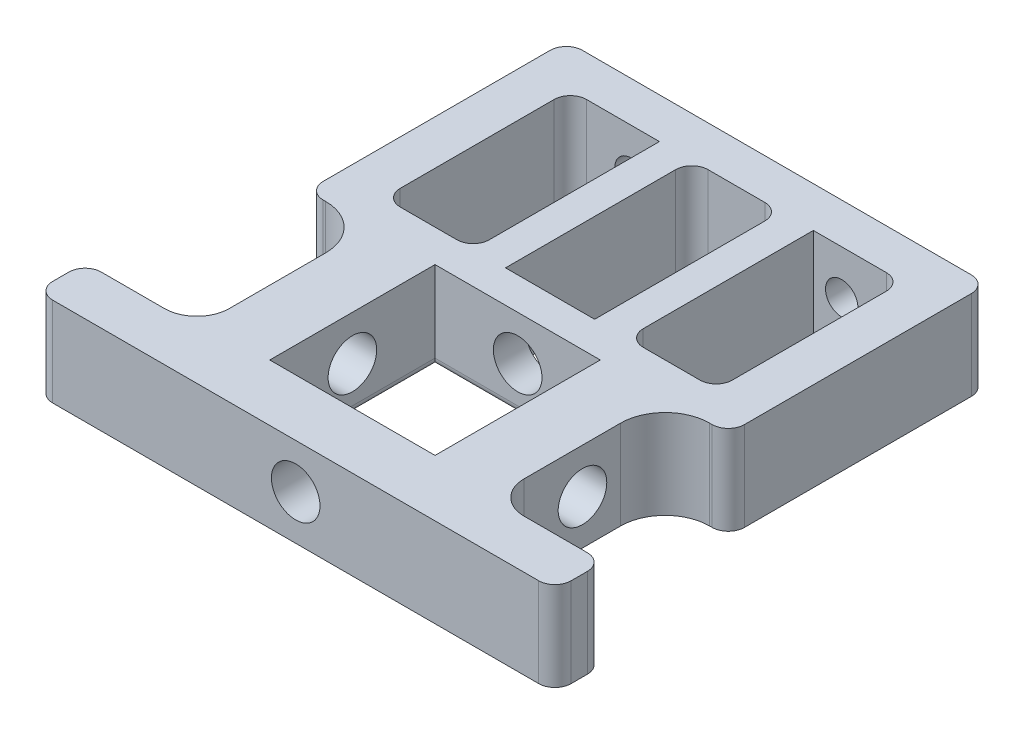
SolidWorks part; units mm, degrees
ref_plane "Front Plane" through (0, 0, 0) normal (0, 0, 1) x (1, 0, 0)
ref_plane "Top Plane" through (0, 0, 0) normal (0, 1, 0) x (1, 0, 0)
ref_plane "Right Plane" through (0, 0, 0) normal (1, 0, 0) x (0, 0, -1)
sketch "Sketch1" plane through (0, 0, 0) normal (0, 1, 0) x (1, 0, 0)
  line L0 (26, 0) -> (26, -32) construction
  line L1 (0, 0) -> (52, 0)
  line L2 (0, 0) -> (0, -32)
  line L3 (0, -32) -> (52, -32)
  line L4 (52, 0) -> (52, -32)
  line L5 (13, 8.9891) -> (13, -5) construction
  line L6 (20.5, -5) -> (31.5, -5)
  line L7 (20.5, -5) -> (20.5, -28)
  line L8 (20.5, -28) -> (31.5, -28)
  line L9 (31.5, -5) -> (31.5, -28)
  line L10 (46.5, -28) -> (35.5, -28)
  line L11 (5.5, -5) -> (16.5, -5)
  line L12 (5.5, -5) -> (5.5, -28)
  line L13 (5.5, -28) -> (16.5, -28)
  line L14 (16.5, -5) -> (16.5, -28)
  line L15 (15.8, -32) -> (36.2, -32)
  line L16 (15.8, -32) -> (15.8, -52.4)
  line L17 (15.8, -52.4) -> (36.2, -52.4)
  line L18 (36.2, -32) -> (36.2, -52.4)
  line L19 (7.8, -32) -> (44.2, -32)
  line L20 (7.8, -32) -> (7.8, -59.4)
  line L21 (7.8, -59.4) -> (44.2, -59.4)
  line L22 (44.2, -32) -> (44.2, -59.4)
  line L23 (35.5, -5) -> (35.5, -28)
  line L24 (46.5, -5) -> (35.5, -5)
  line L25 (46.5, -5) -> (46.5, -28)
  dimension "D1" = 52
  dimension "D2" = 32
  dimension "D3" = 5.5
  dimension "D4" = 5.5
  dimension "D5" = 5
  dimension "D6" = 4
  dimension "D7" = 13
  dimension "D8" = 5
  dimension "D9" = 4
  dimension "D10" = 4
  dimension "D11" = 5.5
  dimension "D12" = 10.2
  dimension "D13" = 10.2
  dimension "D14" = 20.4
  dimension "D15" = 8
  dimension "D16" = 8
  dimension "D17" = 7
extrude "Boss-Extrude1" add sketch "Sketch1" along normal blind 11 contours L4 L1 L2 L3 L6 L9 L8 L7 L11 L14 L13 L12 L24 L25 L10 L23 | L22 L3 L18 L17 L16 L20 L21
sketch "Sketch2" plane through (0, 0, 0) normal (0, 0, -1) x (-1, 0, 0)
  line L0 (-26, 11) -> (-26, 0) construction
  line L1 (0, 11) -> (-52, 11) construction
  line L2 (0, 0) -> (-52, 0) construction
  line L3 (-39, 11) -> (-39, 0) construction
  line L4 (-52, 5.5) -> (0, 5.5) construction
  line L5 (-52, 11) -> (-52, 0) construction
  line L6 (0, 11) -> (0, 0) construction
  circle A0 centre (-39, 5.5) radius 2
  circle A1 centre (-13, 5.5) radius 2
  dimension "D1" = 13
extrude "Cut-Extrude1" cut sketch "Sketch2" against normal up to next
sketch "Sketch3" plane through (15.8, 0, 0) normal (1, 0, 0) x (0, 0, -1)
  line L0 (-42.2, 0) -> (-42.2, 11) construction
  line L1 (-32, 0) -> (-52.4, 0) construction
  line L2 (-32, 11) -> (-52.4, 11) construction
  line L3 (-32, 5.5) -> (-52.4, 5.5) construction
  line L4 (-32, 11) -> (-32, 0) construction
  line L5 (-52.4, 11) -> (-52.4, 0) construction
  circle A0 centre (-42.2, 5.5) radius 3
  dimension "D1" = 6
extrude "Cut-Extrude2" cut sketch "Sketch3" against normal up to next and the other way up to next
sketch "Sketch4" plane through (0, 0, 32) normal (0, 0, 1) x (1, 0, 0)
  line L0 (26, 0) -> (26, 11) construction
  line L1 (15.8, 0) -> (36.2, 0) construction
  line L2 (15.8, 11) -> (36.2, 11) construction
  line L3 (36.2, 5.5) -> (15.8, 5.5) construction
  line L4 (36.2, 11) -> (36.2, 0) construction
  line L5 (15.8, 11) -> (15.8, 0) construction
  circle A0 centre (26, 5.5) radius 3
extrude "Cut-Extrude3" cut sketch "Sketch4" against normal up to next and the other way up to next
fillet "Fillet1" radius 2 12 edges at (20.5, 5.5, 5) (31.5, 5.5, 5) (16.5, 5.5, 28) (35.5, 5.5, 28) (5.5, 5.5, 28) (46.5, 5.5, 28) (46.5, 5.5, 5) (5.5, 5.5, 5) (0, 5.5, 32) (52, 5.5, 32) (0, 5.5, 0) (52, 5.5, 0)
fillet "Fillet2" radius 5.5 2 edges at (7.8, 5.5, 32) (44.2, 5.5, 32)
fillet "Fillet3" radius 1 4 edges at (26, 0, 52.4) (15.8, 0, 42.2) (26, 0, 32) (36.2, 0, 42.2)
sketch "Sketch5" plane through (0, 0, 0) normal (0, -1, 0) x (1, 0, 0)
  line L0 (26, 59.4) -> (26, 31) construction
  line L1 (7.8, 59.4) -> (-6, 59.4)
  line L2 (7.8, 59.4) -> (7.8, 53.4)
  line L3 (7.8, 53.4) -> (-6, 53.4)
  line L4 (-6, 59.4) -> (-6, 53.4)
  line L5 (7.8, 59.4) -> (44.2, 59.4) construction
  line L6 (37.2, 31) -> (14.8, 31) construction
  line L7 (58, 59.4) -> (58, 53.4)
  line L8 (44.2, 53.4) -> (58, 53.4)
  line L9 (44.2, 59.4) -> (44.2, 53.4)
  line L10 (44.2, 59.4) -> (58, 59.4)
  dimension "D1" = 6
  dimension "D2" = 32
extrude "Boss-Extrude2" add sketch "Sketch5" against normal blind 11
fillet "Fillet4" radius 4 2 edges at (44.2, 5.5, 53.4) (7.8, 5.5, 53.4)
fillet "Fillet5" radius 2 4 edges at (58, 5.5, 59.4) (58, 5.5, 53.4) (-6, 5.5, 59.4) (-6, 5.5, 53.4)
